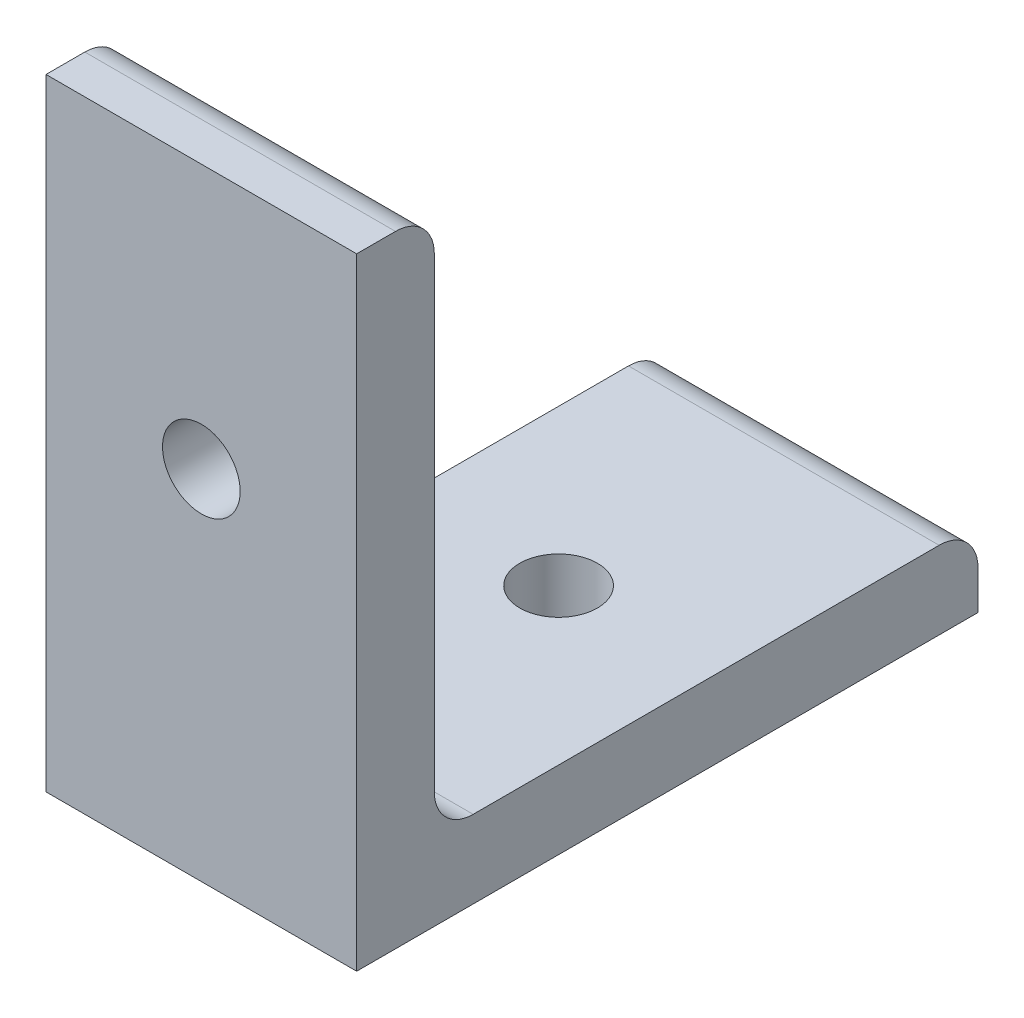
SolidWorks part; units mm, degrees
material "6061-T6 (SS)"
ref_plane "Front Plane" through (0, 0, 0) normal (0, 0, 1) x (1, 0, 0)
ref_plane "Top Plane" through (0, 0, 0) normal (0, 1, 0) x (1, 0, 0)
ref_plane "Right Plane" through (0, 0, 0) normal (1, 0, 0) x (0, 0, -1)
sketch "Sketch1" plane through (0, 0, 0) normal (1, 0, 0) x (0, 0, -1)
  line L0 (0, 0) -> (50.8, 0)
  line L1 (50.8, 0) -> (50.8, 6.35)
  line L2 (50.8, 6.35) -> (6.35, 6.35)
  line L3 (6.35, 6.35) -> (6.35, 50.8)
  line L4 (6.35, 50.8) -> (0, 50.8)
  line L5 (0, 50.8) -> (0, 0)
  dimension "D1" = 50.8
  dimension "D2" = 6.35
  dimension "D3" = 6.35
  dimension "D4" = 50.8
extrude "Boss-Extrude1" add sketch "Sketch1" along normal blind 25.4
sketch "Sketch2" plane through (0, 0, 0) normal (0, 0, 1) x (1, 0, 0)
  line L0 (25.4, 50.8) -> (0, 50.8) construction
  line L1 (0, 50.8) -> (0, 0) construction
  circle A0 centre (12.7, 29.21) radius 3.175
  dimension "D1" = 6.35
  dimension "D2" = 21.59
  dimension "D3" = 12.7
extrude "Cut-Extrude1" cut sketch "Sketch2" against normal up to next
sketch "Sketch3" plane through (0, 6.35, 0) normal (0, 1, 0) x (1, 0, 0)
  line L0 (25.4, 50.8) -> (0, 50.8) construction
  line L1 (0, 50.8) -> (0, 6.35) construction
  circle A0 centre (12.7, 29.21) radius 3.175
  dimension "D1" = 6.35
  dimension "D2" = 21.59
  dimension "D3" = 12.7
extrude "Cut-Extrude2" cut sketch "Sketch3" against normal up to next
fillet "Fillet1" radius 3.175 1 edges at (12.7, 6.35, -6.35)
fillet "Fillet2" radius 3.175 2 edges at (12.7, 50.8, -6.35) (12.7, 6.35, -50.8)
